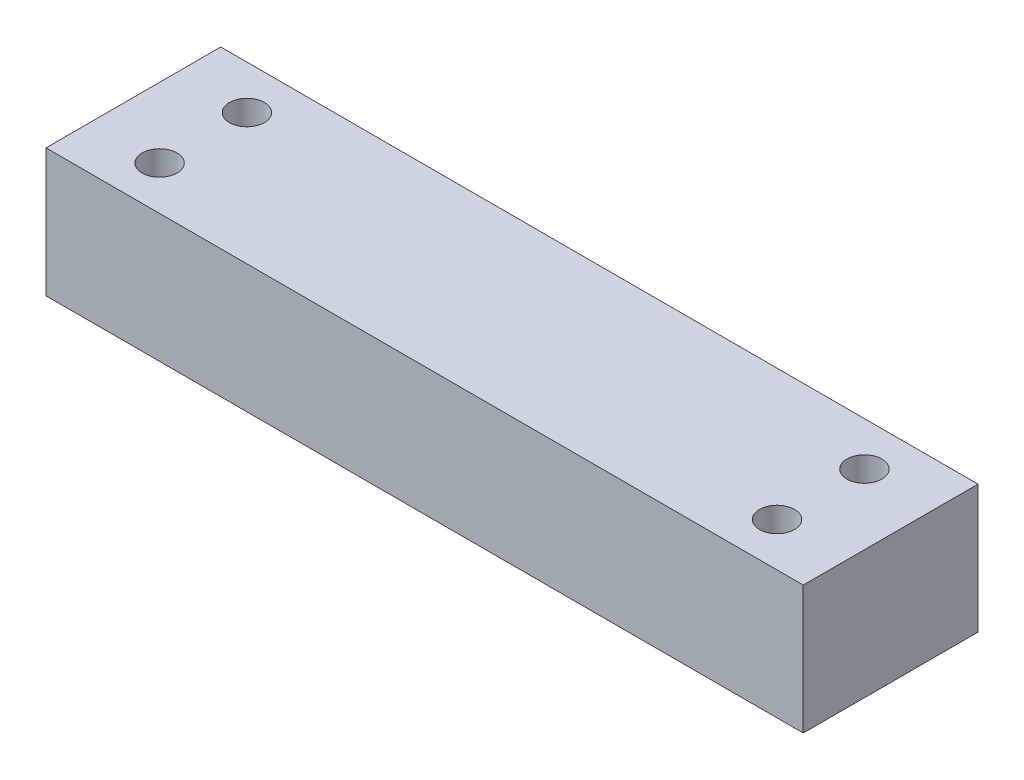
SolidWorks part; units mm, degrees
ref_plane "Front Plane" through (0, 0, 0) normal (0, 0, 1) x (1, 0, 0)
ref_plane "Top Plane" through (0, 0, 0) normal (0, 1, 0) x (1, 0, 0)
ref_plane "Right Plane" through (0, 0, 0) normal (1, 0, 0) x (0, 0, -1)
sketch "Sketch1" plane through (0, 0, 0) normal (0, 1, 0) x (1, 0, 0)
  line L0 (-65, 0) -> (65, 0) construction
  line L1 (-65, 15) -> (65, 15)
  line L2 (-65, 15) -> (-65, -15)
  line L3 (-65, -15) -> (65, -15)
  line L4 (65, 15) -> (65, -15)
  circle A0 centre (-53, 7.5) radius 3
  circle A1 centre (-53, -7.5) radius 3
  circle A2 centre (53, 7.5) radius 3
  circle A3 centre (53, -7.5) radius 3
  point P4 (0, 15)
  point P5 (-65, 0)
  dimension "D3" = 15
  dimension "D7" = 15
  dimension "D1" = 130
  dimension "D2" = 30
  dimension "D4" = 12
  dimension "D5" = 7.5
  dimension "D6" = 12
extrude "Boss-Extrude1" add sketch "Sketch1" along normal blind 22
